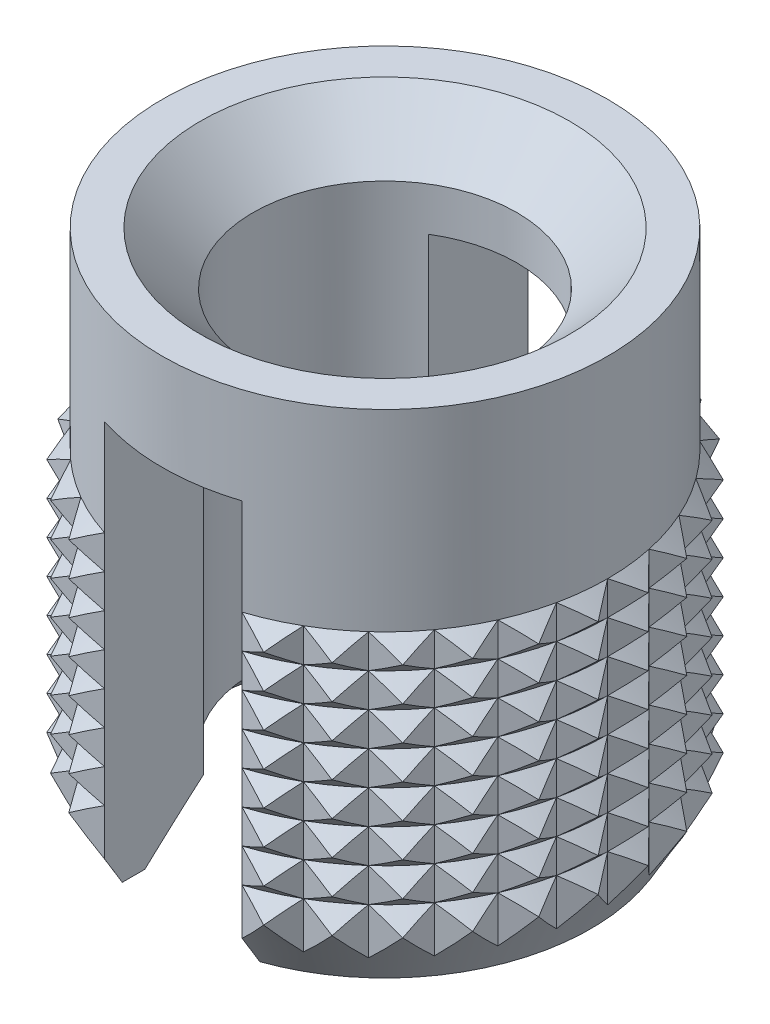
SolidWorks part; units mm, degrees
ref_plane "Front Plane" through (0, 0, 0) normal (0, 0, 1) x (1, 0, 0)
ref_plane "Top Plane" through (0, 0, 0) normal (0, 1, 0) x (1, 0, 0)
ref_plane "Right Plane" through (0, 0, 0) normal (1, 0, 0) x (0, 0, -1)
sketch "Sketch2" plane through (0, 0, 0) normal (0, 0, 1) x (1, 0, 0)
  line L0 (-2.11, 4.78) -> (-2.11, 2.9543)
  line L1 (-2.11, 2.9543) -> (-2.27, 2.7943)
  line L3 (-2.27, 0.5543) -> (-1.95, 0)
  line L4 (-1.95, 0) -> (-1.75, 0)
  line L5 (-1.75, 0) -> (-1.25, 0.5)
  line L6 (-1.25, 0.5) -> (-1.25, 4.28)
  line L7 (-1.25, 4.28) -> (-1.75, 4.78)
  line L8 (-1.75, 4.78) -> (-2.11, 4.78)
  line L9 (0, 0) -> (0, 4.78) construction
  line L10 (-2.27, 2.7943) -> (-2.11, 2.6343)
  line L11 (-2.11, 2.6343) -> (-2.27, 2.4743)
  line L12 (-2.27, 2.4743) -> (-2.11, 2.3143)
  line L13 (-2.11, 2.3143) -> (-2.27, 2.1543)
  line L14 (-2.27, 2.1543) -> (-2.11, 1.9943)
  line L15 (-2.11, 1.9943) -> (-2.27, 1.8343)
  line L16 (-2.27, 1.8343) -> (-2.11, 1.6743)
  line L17 (-2.11, 1.6743) -> (-2.27, 1.5143)
  line L18 (-2.27, 1.5143) -> (-2.11, 1.3543)
  line L19 (-2.11, 1.3543) -> (-2.27, 1.1943)
  line L20 (-2.27, 1.1943) -> (-2.11, 1.0343)
  line L21 (-2.11, 1.0343) -> (-2.27, 0.8743)
  line L22 (-2.27, 0.8743) -> (-2.11, 0.7143)
  line L23 (-2.11, 0.7143) -> (-2.27, 0.5543)
  point P20 (-2.11, 0.2771)
  dimension "D1" = 4.78
  dimension "D2" = 1.25
  dimension "D3" = 1.75
  dimension "D4" = 135
  dimension "D5" = 120
  dimension "D6" = 2.11
  dimension "D7" = 0.2
revolve "Revolve1" add sketch "Sketch2" angle 360 about L9
sketch "Sketch3" plane through (0, 4.78, 0) normal (0, 1, 0) x (1, 0, 0)
  line L0 (-0.2206, 2.0984) -> (0, 2.27)
  line L1 (0, 2.27) -> (0.2206, 2.0984)
  line L2 (-0.2206, 2.0984) -> (0, 0) construction
  line L3 (0, 0) -> (0.2206, 2.0984) construction
  line L4 (-0.2206, 2.0984) -> (-0.2892, 2.7511)
  line L5 (-0.2892, 2.7511) -> (0.2892, 2.7511)
  line L6 (0.2892, 2.7511) -> (0.2206, 2.0984)
  circle A0 centre (0, 0) radius 2.11 construction
  circle A3 centre (0, 0) radius 2.27 construction
  dimension "D1" = 12
extrude "Cut-Extrude1" cut sketch "Sketch3" against normal through all both and the other way through all
pattern_circular "CirPattern1" count 30 over 360 about axis through (0, 0, 0) along (0, 1, 0) of "Cut-Extrude1"
sketch "Sketch4" plane through (0, 0, 0) normal (0, 0, 1) x (1, 0, 0)
  line L1 (-0.652, 3.8671) -> (0.652, 3.8671)
  line L2 (0.652, 3.8671) -> (0.652, 2.9543)
  line L3 (0.652, 2.9543) -> (0.652, 0)
  line L4 (0.652, 0) -> (-0.652, 0)
  line L5 (-0.652, 0) -> (-0.652, 3.8671)
  line L6 (0.652, 3.8671) -> (2.11, 3.8671) construction
  line L7 (2.11, 2.9543) -> (2.11, 4.78) construction
  line L8 (-1.95, 0) -> (1.95, 0) construction
extrude "Cut-Extrude2" cut sketch "Sketch4" against normal through all both and the other way through all
